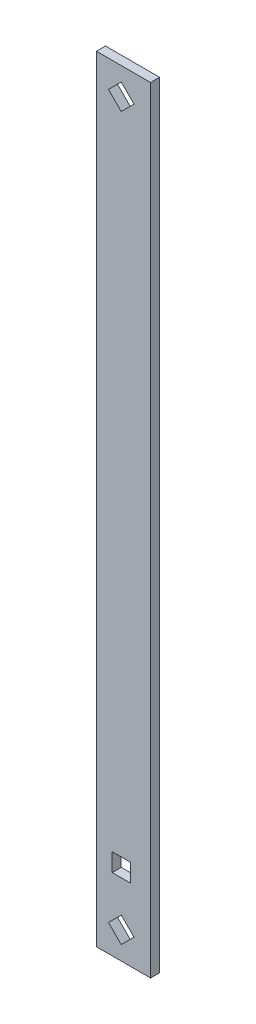
SolidWorks part; units mm, degrees
ref_plane "Top" through (0, 0, 0) normal (0, 0, 1) x (1, 0, 0)
ref_plane "Front" through (0, 0, 0) normal (0, 1, 0) x (1, 0, 0)
ref_plane "Right" through (0, 0, 0) normal (1, 0, 0) x (0, 0, -1)
sketch "Profile Sketch" plane through (-13.8341, 0, -105.7567) normal (0, 1, 0) x (-1, 0, 0)
  line L1 (-3, 0) -> (3, 0)
  line L2 (-3, 0) -> (-3, 1)
  line L3 (-3, 1) -> (3, 1)
  line L4 (3, 0) -> (3, 1)
  line L5 (0, 1) -> (0, 0) construction
  line L6 (-3, 0.5) -> (3, 0.5) construction
  point P128 (0, 0.5)
  dimension "Height" = 1
  dimension "Width" = 6
extrude "Profile Extrude" add sketch "Profile Sketch" along normal blind 86
sketch "Fiducial Sketch" plane through (0, 0, -104.7567) normal (0, 0, 1) x (1, 0, 0)
  line L0 (-14.0841, 3) -> (-12.6698, 3) construction
  line L1 (-12.6698, 3) -> (-14.0841, 4.4142)
  line L2 (-14.0841, 4.4142) -> (-15.4983, 3)
  line L3 (-15.4983, 3) -> (-14.0841, 1.5858)
  line L4 (-14.0841, 1.5858) -> (-12.6698, 3)
  line L9 (-14.0841, 3) -> (-14.0841, 0) construction
  line L10 (-16.8341, 0) -> (-10.8341, 0) construction
  line L17 (-16.8341, 86) -> (-16.8341, 0) construction
  circle A0 centre (-14.0841, 3) radius 1.4142 construction
  point P85 (-14.0841, 4)
  dimension "D1" = 2.8284
  dimension "Fiducial Y Spacing" = 3
  dimension "Fiducial X Position" = 2.75
extrude "Fiducial Cut" cut sketch "Fiducial Sketch" against normal through all
ref_plane "Mid Plane" through (0, 43, 0) normal (0, -1, 0) x (-1, 0, 0)
mirror "Fiducial Mirror" about plane through (0, 43, 0) normal (0, -1, 0) of "Fiducial Cut"
sketch "Fiducial 1 Indicator Sketch" plane through (0, 0, -104.7567) normal (0, 0, 1) x (1, 0, 0)
  line L9 (-14.0841, 3) -> (-14.0841, 0) construction
  line L11 (-15.0841, 6) -> (-13.0841, 6) construction
  line L12 (-15.0841, 10) -> (-13.0841, 10)
  line L13 (-15.0841, 10) -> (-15.0841, 8)
  line L14 (-15.0841, 8) -> (-13.0841, 8)
  line L15 (-13.0841, 10) -> (-13.0841, 8)
  line L16 (-14.0841, 8) -> (-14.0841, 10) construction
  line L17 (-15.0841, 9) -> (-13.0841, 9) construction
  line L18 (-16.8341, 0) -> (-10.8341, 0) construction
  line L19 (-16.8341, 86) -> (-16.8341, 0) construction
  point P85 (-14.0841, 9)
  dimension "Fiducial X Position" = 2.75
  dimension "D2" = 2.8284
extrude "Indicator of Fiducial 1 Cut" cut sketch "Fiducial 1 Indicator Sketch" against normal through all
equation "\"D1@Fiducial Sketch\" = 2 * sqr ( 2 ) "
equation "\"D2@Fiducial 1 Indicator Sketch\" = 2 * sqr ( 2 ) "
